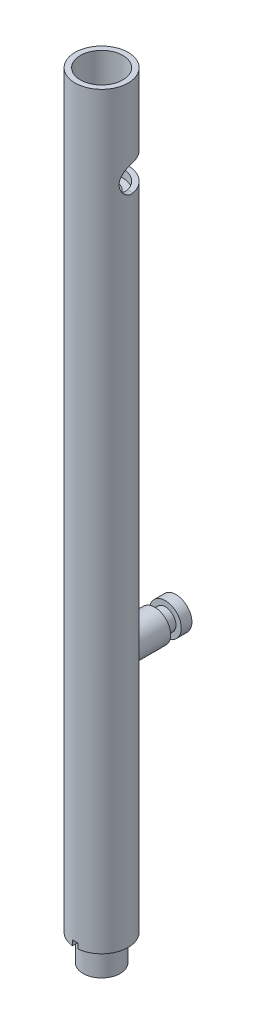
SolidWorks part; units mm, degrees
material "1060 Alloy"
ref_plane "Front Plane" through (0, 0, 0) normal (0, 0, 1) x (1, 0, 0)
ref_plane "Top Plane" through (0, 0, 0) normal (0, 1, 0) x (1, 0, 0)
ref_plane "Right Plane" through (0, 0, 0) normal (1, 0, 0) x (0, 0, -1)
sketch "Sketch1" plane through (0, 0, 0) normal (0, 1, 0) x (1, 0, 0)
  circle A0 centre (0, 0) radius 5
  dimension "D1" = 10
extrude "Boss-Extrude1" add sketch "Sketch1" along normal blind 150
ref_plane "Plane1" through (0, 0, -5) normal (0, 0, 1) x (1, 0, 0)
sketch "Sketch4" plane through (0, 0, -5) normal (0, 0, 1) x (1, 0, 0)
  line L0 (0, 0) -> (0, 45)
  circle A0 centre (0, 45) radius 3
  dimension "D1" = 6
extrude "Boss-Extrude2" add sketch "Sketch4" against normal blind 5 and the other way up to surface separate body other way up to face at (0, 150, 5)
sketch "Sketch5" plane through (0, 0, -10) normal (0, 0, -1) x (-1, 0, 0)
  circle A0 centre (0, 45.0741) radius 2
  dimension "D1" = 4
extrude "Boss-Extrude3" add sketch "Sketch5" along normal blind 2
sketch "Sketch6" plane through (0, 0, -12) normal (0, 0, -1) x (-1, 0, 0)
  circle A2 centre (0, 45.0741) radius 3
extrude "Boss-Extrude4" add sketch "Sketch6" along normal blind 2
sketch "Sketch7" plane through (0, 0, 0) normal (0, -1, 0) x (1, 0, 0)
  circle A0 centre (0, 0) radius 3.5
extrude "Boss-Extrude5" add sketch "Sketch7" along normal blind 5
sketch "Sketch8" plane through (0, 150, 0) normal (0, 1, 0) x (1, 0, 0)
  circle A0 centre (0, 0) radius 3.5
extrude "Boss-Extrude6" add sketch "Sketch8" along normal blind 5
sketch "Sketch9" plane through (0, 155, 0) normal (0, 1, 0) x (1, 0, 0)
  circle A0 centre (0, 0) radius 2.75
extrude "Cut-Extrude1" cut sketch "Sketch9" against normal blind 168
sketch "Sketch11" [suppressed] plane through (0, 0, 0) normal (0, -1, 0) x (-1, 0, 0)
  line L0 (3.5, 0) -> (5, 0)
  circle A0 centre (0, 0) radius 3.5 construction
  circle A1 centre (0, 0) radius 3.5 construction
  circle A2 centre (0, 0) radius 5 construction
ref_plane "Plane2" through (0, 0, 5) normal (0, 0, 1) x (1, 0, 0)
sketch "Sketch14" plane through (0, 0, 5) normal (0, 0, 1) x (1, 0, 0)
  line L0 (0, 0) -> (0.5, 0)
  line L1 (-3.5, 0) -> (3.5, 0) construction
  line L2 (0, 0) -> (-0.5, 0)
  line L3 (-0.5, 0) -> (-0.5, 1)
  line L4 (-0.5, 1) -> (0.5, 1)
  line L5 (0.5, 1) -> (0.5, 0)
extrude "Cut-Extrude4" cut sketch "Sketch14" against normal up to surface (1.5 mm away)
ref_plane "Plane3" through (-0.5, 1, 4.9749) normal (0.995, 0, 0.1) x (0.1, 0, -0.995)
sketch "Sketch16" plane through (0, 150, 0) normal (0, 1, 0) x (1, 0, 0)
  line L0 (0.5, -3.5) -> (0.5, -4.9749)
  line L1 (0.5, -3.5) -> (0.5, -3.4641)
  line L2 (0, -9.35) -> (0, 9.35) construction
  line L3 (-0.5, -3.5) -> (-0.5, -3.4641)
  line L4 (-0.5, -3.5) -> (-0.5, -4.9749)
  arc A0 (-0.5, -3.4641) -> (0.5, -3.4641) centre (0, 0) ccw
  arc A1 (-0.5, -4.9749) -> (0.5, -4.9749) centre (0, 0) ccw
extrude "Boss-Extrude7" add sketch "Sketch16" along normal blind 1
ref_plane "Plane4" through (-5, 0, 0) normal (1, 0, 0) x (0, 0, -1)
sketch "Sketch18" plane through (-5, 0, 0) normal (1, 0, 0) x (0, 0, -1)
  line L2 (1.0125, 127.5) -> (8.0125, 127.5)
  line L3 (8.0125, 127.5) -> (8.0125, 122.5)
  line L4 (8.0125, 122.5) -> (1.0125, 122.5)
  arc A1 (1.0125, 127.5) -> (1.0125, 122.5) centre (1.0125, 125) ccw
extrude "Cut-Extrude5" cut sketch "Sketch18" along normal blind 18
sketch "Sketch19" plane through (0, 155, 0) normal (0, 1, 0) x (1, 0, 0)
  circle A0 centre (0, 0) radius 4
extrude "Cut-Extrude6" cut sketch "Sketch19" against normal blind 34
sketch "Sketch20" plane through (0, 151, 0) normal (0, 1, 0) x (1, 0, 0)
  line L1 (12.2047, -14.1275) -> (-12.2047, -14.1275)
  line L2 (12.2047, -14.1275) -> (12.2047, 14.1275)
  line L3 (12.2047, 14.1275) -> (-12.2047, 14.1275)
  line L4 (-12.2047, -14.1275) -> (-12.2047, 14.1275)
  line L5 (12.2047, -14.1275) -> (-12.2047, 14.1275) construction
  line L6 (12.2047, 14.1275) -> (-12.2047, -14.1275) construction
  point P0 (0, 0)
extrude "Cut-Extrude7" cut sketch "Sketch20" against normal blind 10
ref_plane "Plane5" through (-2.5, 0, 0) normal (1, 0, 0) x (0, 0, -1)
sketch "Sketch22" plane through (-2.5, 0, 0) normal (1, 0, 0) x (0, 0, -1)
  line L1 (10, 43.0741) -> (10, 47.0741) construction
  line L6 (10, 45.0741) -> (12, 45.0741)
  line L8 (10, 45.0741) -> (10, 44.5741)
  line L9 (12, 45.0741) -> (12, 44.5741)
  line L10 (12, 44.5741) -> (10, 44.5741)
  point P5 (10, 45.0741)
extrude "Boss-Extrude8" add sketch "Sketch22" along normal up to surface (0.5 mm away) up to face at (-2, 45.0741, -12)
